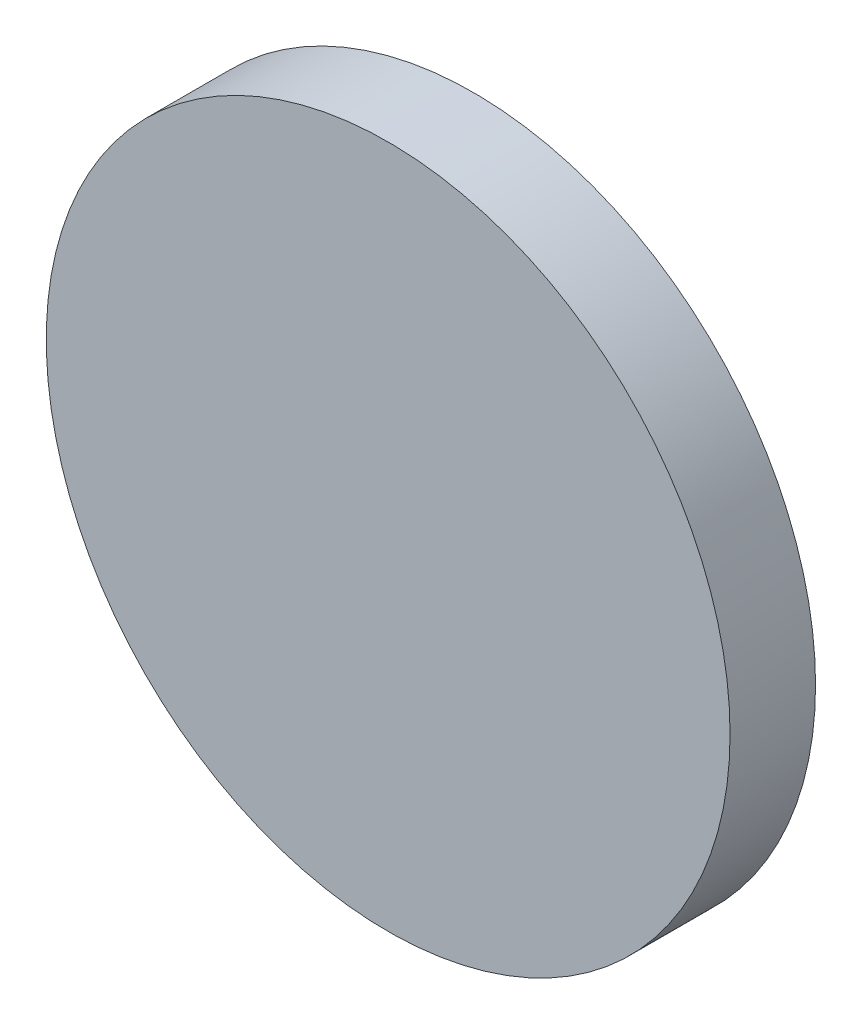
SolidWorks part; units mm, degrees
ref_plane "前视基准面" through (0, 0, 0) normal (0, 0, 1) x (1, 0, 0)
ref_plane "上视基准面" through (0, 0, 0) normal (0, 1, 0) x (1, 0, 0)
ref_plane "右视基准面" through (0, 0, 0) normal (1, 0, 0) x (0, 0, -1)
sketch "草图1" plane through (0, 0, 0) normal (0, 0, 1) x (1, 0, 0)
  circle A0 centre (0, 0) radius 10
  dimension "D1" = 20
extrude "凸台-拉伸3" add sketch "草图1" along normal blind 2.5
sketch "草图5" plane through (0, 0, 0) normal (0, 0, -1) x (-1, 0, 0)
  circle A0 centre (0, 0) radius 4.5
  dimension "D1" = 9
extrude "凸台-拉伸4" add sketch "草图5" along normal blind 2
